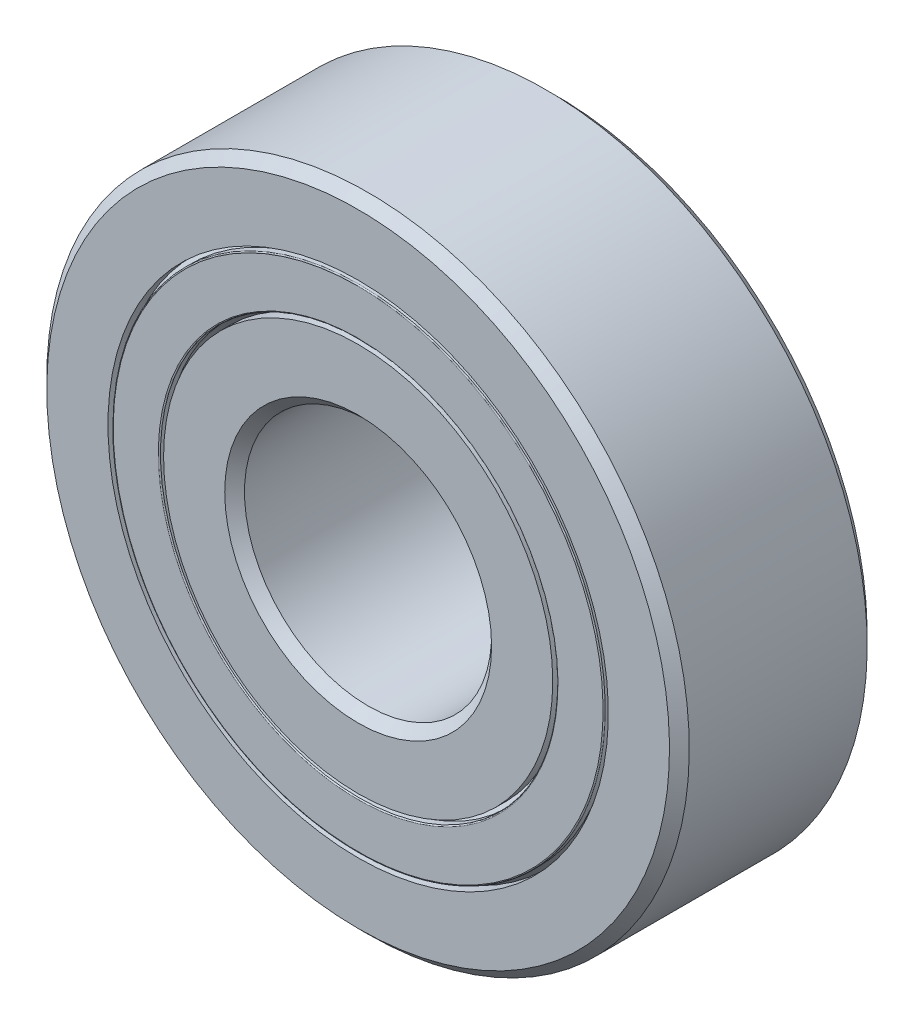
SolidWorks part; units mm, degrees
ref_plane "Front Plane" through (0, 0, 0) normal (0, 0, 1) x (1, 0, 0)
ref_plane "Top Plane" through (0, 0, 0) normal (0, 1, 0) x (1, 0, 0)
ref_plane "Right Plane" through (0, 0, 0) normal (1, 0, 0) x (0, 0, -1)
sketch "Sketch1" plane through (0, 0, 0) normal (0, 0, 1) x (1, 0, 0)
  line L0 (-13, 0) -> (13, 0) construction
  line L1 (-5, 0) -> (5, 0) construction
  circle A0 centre (0, 0) radius 5 construction
  circle A1 centre (0, 0) radius 13 construction
  point P3 (0, 0)
  point P6 (0, 0)
  point P7 (0, -5)
  point P11 (0, -13)
  point P12 (0, 5)
  point P13 (0, 13)
  dimension "OD" = 26
  dimension "ID" = 10
sketch "Sketch2" plane through (0, 0, 0) normal (1, 0, 0) x (0, 0, -1)
  line L0 (-4, 13) -> (4, 13) construction
  line L1 (0, 13) -> (0, -13) construction
  line L2 (3.6, 13) -> (-3.6, 13)
  line L3 (-3.6, 13) -> (-4, 12.6)
  line L4 (-4, 12.6) -> (-4, 10.125)
  line L5 (-4, 10.125) -> (-1.7778, 10.125)
  line L6 (4, 10.125) -> (1.7778, 10.125)
  line L7 (4, 12.6) -> (4, 10.125)
  line L8 (3.6, 13) -> (4, 12.6)
  line L9 (0, 13) -> (0, 9) construction
  line L10 (0, 9) -> (0, 5) construction
  line L11 (0, 13) -> (0, -13) construction
  line L12 (-4, 0) -> (4, 0) construction
  line L13 (4, 5) -> (-4, 5) construction
  line L14 (0, 11.1038) -> (0, 6.8962) construction
  line L15 (-4, -5) -> (4, -5) construction
  line L16 (-4, 5) -> (-4, -5) construction
  line L17 (4, 13) -> (4, -13) construction
  line L18 (-4, 10.125) -> (-4, 10.0125) construction
  line L19 (-4, 10.0125) -> (-4, 9.9) construction
  line L20 (-4, 9.9) -> (-4, 9.7875) construction
  line L21 (-4, 9.7875) -> (-4, 9.675) construction
  line L22 (-4, 9.675) -> (-4, 9.5625) construction
  line L24 (-2.8889, 10.125) -> (-2.8889, 9) construction
  arc A0 (-1.7778, 10.125) -> (1.7778, 10.125) centre (0, 9) cw
  circle A1 centre (0, 9) radius 2.1038 construction
  point P14 (0, 5)
  point P17 (0, 0)
  point P21 (0, 13)
  point P29 (0, 5)
  point P30 (0, -5)
  point P46 (-2.8889, 9.5625)
  dimension "Width" = 8
  dimension "D1" = 45
  dimension "D2" = 0.4
  dimension "D3" = 3.5556
  dimension "D4" = 1.125
  dimension "For Shaft Diameter" = 10
  dimension "For Housing ID" = 26
sketch "Sketch3" plane through (0, 0, 0) normal (1, 0, 0) x (0, 0, -1)
  line L0 (3.6, 13) -> (4, 12.6) construction
  line L1 (4, 12.6) -> (4, 10.125) construction
  line L2 (4, 10.125) -> (1.7778, 10.125) construction
  line L3 (-4, 10.125) -> (-1.7778, 10.125) construction
  line L4 (-4, 12.6) -> (-4, 10.125) construction
  line L5 (-3.6, 13) -> (-4, 12.6) construction
  line L6 (3.6, 13) -> (-3.6, 13) construction
  line L7 (3.6, 13) -> (4, 12.6)
  line L8 (4, 12.6) -> (4, 10.125)
  line L9 (4, 10.125) -> (1.7778, 10.125)
  line L10 (-4, 10.125) -> (-1.7778, 10.125)
  line L11 (-4, 12.6) -> (-4, 10.125)
  line L12 (-3.6, 13) -> (-4, 12.6)
  line L13 (3.6, 13) -> (-3.6, 13)
  arc A0 (1.7778, 10.125) -> (-1.7778, 10.125) centre (0, 9) ccw construction
  arc A1 (1.7778, 10.125) -> (-1.7778, 10.125) centre (0, 9) ccw
revolve "Revolve1" add sketch "Sketch3" angle 360 about L12
sketch "Sketch4" plane through (0, 0, 0) normal (1, 0, 0) x (0, 0, -1)
  line L0 (0, 13) -> (0, -13) construction
  line L1 (0, 13) -> (0, -13) construction
  line L2 (-3.6, 5) -> (-4, 5.4)
  line L3 (-4, 5.4) -> (-4, 7.875)
  line L5 (-4, 7.875) -> (-1.7778, 7.875)
  line L6 (-3.6, 5) -> (3.6, 5)
  line L8 (3.6, 5) -> (4, 5.4)
  line L10 (4, 5.4) -> (4, 7.875)
  line L11 (4, 7.875) -> (1.7778, 7.875)
  line L12 (-4, 12.6) -> (-4, 10.125) construction
  line L13 (3.6, 13) -> (4, 12.6) construction
  line L15 (4, -12.6) -> (4, 12.6) construction
  line L16 (3.6, 13) -> (3.6, -13) construction
  arc A1 (1.7778, 7.875) -> (-1.7778, 7.875) centre (0, 9) cw
  circle A2 centre (0, 9) radius 2.1038 construction
  point P1 (0, 5)
revolve "Revolve2" add sketch "Sketch4" angle 360 about L12
sketch "Sketch5" plane through (0, 0, 0) normal (1, 0, 0) x (0, 0, -1)
  line L0 (-2.1038, 9) -> (2.1038, 9)
  arc A2 (-2.1038, 9) -> (2.1038, 9) centre (0, 9) cw
  arc A3 (1.7778, 10.125) -> (-1.7778, 10.125) centre (0, 9) ccw construction
revolve "Revolve3" add sketch "Sketch5" angle 360 about L0
sketch "Sketch6" plane through (0, 0, 0) normal (1, 0, 0) x (0, 0, -1)
  line L0 (-4, 10.125) -> (-4, 9.5625) construction
  line L1 (-4, 12.6) -> (-4, -12.6) construction
  line L2 (-4, 9.5625) -> (-4, 9) construction
  line L3 (-4, 9) -> (-4, 8.4375) construction
  line L4 (-4, 8.4375) -> (-4, 7.875) construction
  line L5 (-4, 9.5625) -> (-3.6712, 9.5625) construction
  line L7 (-2.0272, 9.5625) -> (-2.0272, 8.4375) construction
  line L8 (-3.6712, 9.5625) -> (-3.3424, 9.5625) construction
  line L10 (0, 13) -> (0, -13) construction
  line L11 (0, 13) -> (0, -13) construction
  line L12 (-3.3424, 9.5625) -> (-3.0136, 9.5625) construction
  line L13 (-3.0136, 9.5625) -> (-2.6848, 9.5625) construction
  line L14 (-2.6848, 9.5625) -> (-2.356, 9.5625) construction
  line L15 (-2.356, 9.5625) -> (-2.0272, 9.5625) construction
  line L16 (-2.0272, 9.5625) -> (-2.356, 9.5625)
  line L17 (-2.356, 8.4375) -> (-2.6848, 8.4375) construction
  line L18 (-2.356, 8.4375) -> (-2.0272, 8.4375)
  line L19 (-2.6848, 8.4375) -> (-2.6848, 9.5625) construction
  line L20 (-2.5204, 9.5625) -> (-2.5204, 8.4375) construction
  circle A0 centre (0, 9) radius 2.1038 construction
  circle A1 centre (0, 9) radius 2.1038 construction
  arc A2 (-2.356, 9.5625) -> (-2.356, 8.4375) centre (-1.4759, 9) ccw
  arc A3 (-2.0272, 9.5625) -> (-2.0272, 8.4375) centre (0, 9) ccw
  point P28 (-2.5204, 9)
revolve "Revolve4" add sketch "Sketch6" angle 360 about L11
pattern_circular "CirPattern1" count 10 over 360 about axis through (0, 0, 0) along (0, 0, 1) of bodies 134 104
sketch "Sketch7" plane through (0, 0, 0) normal (0, 0, 1) x (1, 0, 0)
  line L0 (0, 7.875) -> (0, 8.25) construction
  line L1 (0, 6.8962) -> (0, 11.1038) construction
  line L2 (0, 8.25) -> (0, 8.625) construction
  line L3 (0, 8.625) -> (0, 9) construction
  line L4 (0, 9) -> (0, 9.375) construction
  line L5 (0, 9.375) -> (0, 9.75) construction
  line L6 (0, 9.75) -> (0, 10.125) construction
  line L7 (0, 12.6) -> (0, 10.125) construction
  line L8 (0, 13) -> (0, -13) construction
  circle A0 centre (0, 0) radius 7.875 construction
  circle A1 centre (0, 0) radius 9
  circle A2 centre (0, 0) radius 9.5625
  point P19 (0, 9.5625)
extrude "Boss-Extrude1" add sketch "Sketch7" along normal mid plane 1.3333 separate body
sketch "Sketch8" plane through (0, 0, 0) normal (1, 0, 0) x (0, 0, -1)
  line L0 (-4, 10.0125) -> (-4, 9.9) construction
  line L1 (-4, 9.9563) -> (-3.7037, 9.9563)
  line L2 (-4, 9.9563) -> (-4, 8.0437)
  line L3 (-4, 8.0437) -> (-3.7037, 8.0437)
  line L4 (-3.5556, 9.9563) -> (-3.5556, 8.0437)
  line L5 (0, 13) -> (0, 9) construction
  line L10 (-3.7037, 9.9563) -> (-3.5556, 10.125)
  line L11 (-4, 10.125) -> (-1.7778, 10.125) construction
  line L12 (-3.5556, 10.125) -> (-3.5556, 9.9563)
  line L13 (-3.7037, 8.0437) -> (-3.5556, 7.875)
  line L14 (-3.5556, 7.875) -> (-3.5556, 8.0437)
  line L15 (-4, 10.125) -> (-3.8519, 10.125) construction
  line L16 (4, 9.9563) -> (4, 8.0437)
  line L17 (4, 8.0437) -> (3.7037, 8.0437)
  line L18 (3.7037, 8.0437) -> (3.5556, 7.875)
  line L19 (3.5556, 7.875) -> (3.5556, 8.0437)
  line L20 (3.5556, 9.9563) -> (3.5556, 8.0437)
  line L21 (3.5556, 10.125) -> (3.5556, 9.9563)
  line L22 (3.7037, 9.9563) -> (3.5556, 10.125)
  line L23 (4, 9.9563) -> (3.7037, 9.9563)
  line L24 (-3.8519, 10.125) -> (-3.7037, 10.125) construction
  line L25 (-3.7037, 10.125) -> (-3.5556, 10.125) construction
  line L27 (-4, 7.875) -> (-1.7778, 7.875) construction
  point P23 (-4, 9.9563)
  dimension "D1" = 0.4444
revolve "Revolve5" add sketch "Sketch8" angle 360 about L12
fillet "Fillet1" radius 0.0444 2 edges at (0, -9.9563, 4) (0, -8.0437, 4)
fillet "Fillet2" radius 0.0444 2 edges at (0, -8.0437, -4) (0, -9.9563, -4)
equation "\"D2@Sketch2\" = \"Width@Sketch2\" * .05"
equation "\"D3@Sketch2\" = \"Width@Sketch2\" / 2.25"
equation "\"D4@Sketch2\"=( \"OD@Sketch1\" - \"Width@Sketch2\" )  *.5*.125"
equation "\"D1@Boss-Extrude1\" = \"Width@Sketch2\" / 6"
equation "\"D1@Sketch8\"=(\"Width@Sketch2\"-\"D3@Sketch2\")*.5*.2"
equation "\"D1@Fillet1\"=\"d1@sketch8\"*.1"
equation "\"D1@Fillet2\"=\"d1@fillet1\""
